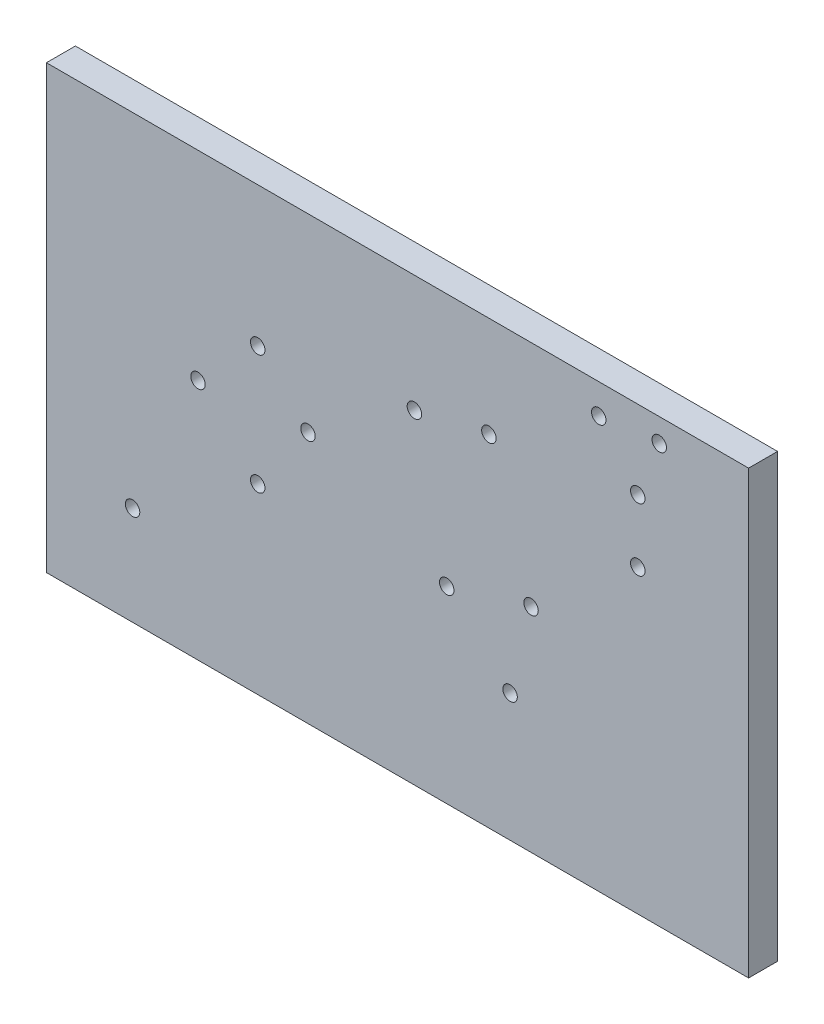
SolidWorks part; units mm, degrees
ref_plane "Front Plane" through (0, 0, 0) normal (0, 0, 1) x (1, 0, 0)
ref_plane "Top Plane" through (0, 0, 0) normal (0, 1, 0) x (1, 0, 0)
ref_plane "Right Plane" through (0, 0, 0) normal (1, 0, 0) x (0, 0, -1)
sketch "Sketch1" plane through (0, 0, 0) normal (0, 0, 1) x (1, 0, 0)
  line L0 (-152.4, 0) -> (155.575, 0) construction
  line L5 (155.575, -88.9) -> (-152.4, -88.9)
  line L7 (155.575, 104.775) -> (-152.4, 104.775)
  line L11 (-152.4, 104.775) -> (-152.4, 0)
  line L12 (-152.4, 0) -> (-152.4, -88.9)
  line L13 (155.575, 104.775) -> (155.575, 0)
  line L14 (155.575, 0) -> (155.575, -88.9)
  point P0 (0, 0)
  dimension "D1" = 307.975
  dimension "D2" = 104.775
  dimension "D3" = 88.9
extrude "Boss-Extrude1" add sketch "Sketch1" along normal blind 12.7
sketch "Sketch3" plane through (0, 0, 12.7) normal (0, 0, 1) x (1, 0, 0)
  line L0 (-119.1393, -11.6254) -> (-112.1791, -63.9728) construction
  line L1 (-59.7336, 69.7092) -> (-59.7336, -35.0658) construction
  line L2 (-126.1858, -70.1907) -> (-84.0696, -51.4941) construction
  line L7 (38.5551, 59.9755) -> (44.7567, 61.3403) construction
  line L9 (-117.5189, -52.2876) -> (-117.5026, -52.3533) construction
  line L10 (-7.3461, 17.3217) -> (-112.1211, 17.3217) construction
  line L11 (-117.5026, -52.3533) -> (-117.4515, -52.3004) construction
  line L12 (-117.4515, -52.3004) -> (-117.5189, -52.2876) construction
  line L13 (-80.2057, -45.5104) -> (-132.9179, -45.5104) construction
  line L16 (-137.2382, -60.5715) -> (-124.5326, -16.2782) construction
  line L17 (5.8847, 52.7858) -> (12.0863, 54.1506) construction
  line L19 (106.976, 46.0754) -> (106.976, 39.7254) construction
  line L26 (47.4281, -18.587) -> (47.4219, -18.6043) construction
  line L27 (47.5514, -18.5541) -> (47.4219, -18.6043) construction
  line L32 (47.4281, -18.587) -> (47.5514, -18.5541) construction
  circle A1 centre (-59.7336, 17.3217) radius 52.3875 construction
  circle A3 centre (106.976, 70.3959) radius 3.175
  circle A5 centre (106.976, 42.9004) radius 3.175
  circle A7 centre (-59.7336, 43.5155) radius 3.175
  circle A18 centre (-59.7336, -8.872) radius 3.175
  circle A19 centre (-85.9274, 17.3217) radius 3.175
  arc A20 (-112.7176, -14.7072) -> (-124.5326, -16.2782) centre (-118.2823, -18.0711) ccw construction
  arc A23 (-84.0696, -51.4941) -> (-84.1442, -39.5754) centre (-86.708, -45.551) ccw construction
  circle A24 centre (-114.6339, -45.5104) radius 3.175
  circle A29 centre (8.9855, 53.4682) radius 3.175
  circle A30 centre (41.6559, 60.6579) radius 3.175
  circle A36 centre (44.7567, -11.6254) radius 22.225 construction
  circle A39 centre (60.143, 4.4124) radius 3.175
  circle A40 centre (50.9527, -32.9693) radius 3.175
  circle A41 centre (23.1743, -6.3194) radius 3.175
  circle A42 centre (-37.6721, 21.75) radius 3.175
  circle A43 centre (93.2282, 56.6481) radius 3.175 [skipped]
  circle A44 centre (120.7237, 56.6481) radius 3.175 [skipped]
  circle A45 centre (89.8428, 91.6832) radius 3.175
  circle A46 centre (116.3712, 94.4995) radius 3.175
  arc A47 (-36.7149, 17.3217) -> (-30.3649, 17.3217) centre (-33.5399, 17.3217) ccw [skipped]
  point P4 (-59.7336, 17.3217)
  point P26 (106.976, 56.6481)
  point P28 (-59.7336, 17.3217)
  point P57 (44.7567, -11.6254)
  point P75 (-117.5189, -52.2876)
  dimension "D3" = 6.35
  dimension "D4" = 6.35
  dimension "D2" = 4
  dimension "D6" = 6.35
  dimension "D7" = 6.35
  dimension "D8" = 6.35
  dimension "D9" = 44.45
  dimension "D10" = 6.35
  dimension "D11" = 3
  dimension "D12" = 6.35
  dimension "D13" = 6.35
  dimension "D5" = 26.1937
  dimension "D15" = 4
extrude "Cut-Extrude1" cut sketch "Sketch3" against normal through all and the other way through all
